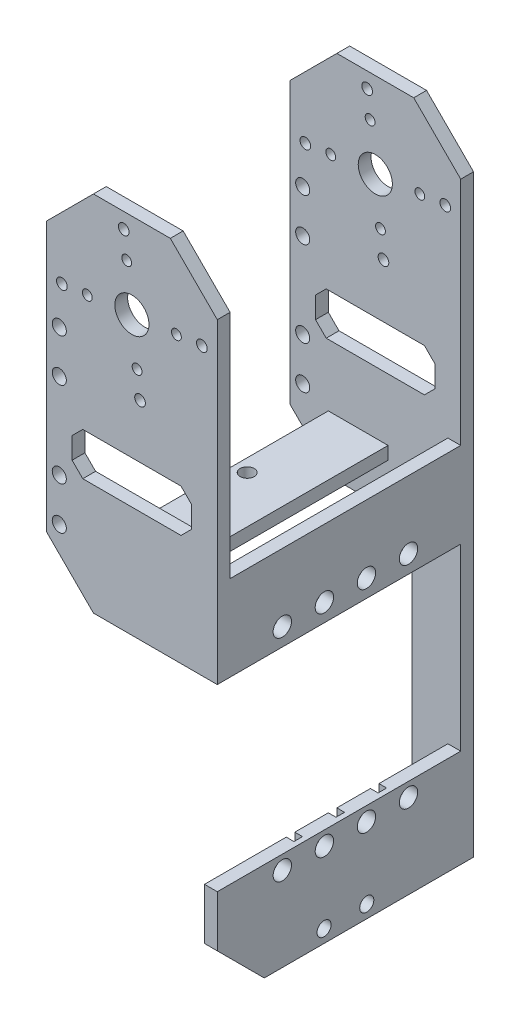
SolidWorks part; units mm, degrees
ref_plane "前视基准面" through (0, 0, 0) normal (0, 0, 1) x (1, 0, 0)
ref_plane "上视基准面" through (0, 0, 0) normal (0, 1, 0) x (1, 0, 0)
ref_plane "右视基准面" through (0, 0, 0) normal (1, 0, 0) x (0, 0, -1)
sketch "草图1" plane through (0, 0, 0) normal (0, 0, 1) x (1, 0, 0)
  line L1 (-20, -30) -> (20, -30)
  line L2 (-20, -30) -> (-20, 30)
  line L3 (-20, 30) -> (20, 30)
  line L4 (20, -30) -> (20, 30)
  line L5 (-20, -30) -> (20, 30) construction
  line L6 (-20, 30) -> (20, -30) construction
  point P0 (0, 0)
  dimension "D1" = 40
  dimension "D2" = 60
extrude "凸台-拉伸1" add sketch "草图1" along normal mid plane 60
chamfer "倒角3" distance 11 angle 45 2 edges at (20, 30, 0) (-20, 30, 0)
sketch "草图6" plane through (0, 30, 0) normal (0, 1, 0) x (1, 0, 0)
  line L0 (20, 30) -> (20, -30) construction
  line L1 (-20, -27) -> (20, -27)
  line L2 (-20, -27) -> (-20, 27)
  line L3 (-20, 27) -> (20, 27)
  line L4 (20, -27) -> (20, 27)
  line L5 (-20, -27) -> (20, 27) construction
  line L6 (-20, 27) -> (20, -27) construction
  line L7 (9, 30) -> (-9, 30) construction
  point P0 (0, 0)
  dimension "D1" = 3
extrude "切除-拉伸4" cut sketch "草图6" against normal blind 80
sketch "草图7" plane through (0, 0, 30) normal (0, 0, 1) x (1, 0, 0)
  line L0 (9, 30) -> (-9, 30) construction
  circle A0 centre (0, 10) radius 4
  dimension "D1" = 8
  dimension "D2" = 20
extrude "切除-拉伸5" cut sketch "草图7" against normal blind 80
sketch "草图9" plane through (0, 0, 30) normal (0, 0, 1) x (1, 0, 0)
  circle A0 centre (-16.3892, 8.0913) radius 1.25
  circle A1 centre (-10.4295, 8.7854) radius 1.15
  circle A2 centre (-1.2146, 20.4295) radius 1.15
  circle A3 centre (-1.9087, 26.3892) radius 1.25
  circle A4 centre (10.4295, 11.2146) radius 1.15
  circle A5 centre (16.3892, 11.9087) radius 1.25
  circle A6 centre (1.2146, -0.4295) radius 1.15
  circle A7 centre (1.9087, -6.3892) radius 1.25
  circle A8 centre (0, 10) radius 4 construction
  point P21 (0, 10)
  dimension "D2" = 2.5
  dimension "D3" = 2.3
  dimension "D1" = 4
extrude "切除-拉伸6" cut sketch "草图9" against normal blind 80
sketch "草图10" plane through (0, -30, 0) normal (0, -1, 0) x (1, 0, 0)
  line L1 (-20, 30) -> (20, 30)
  line L2 (-20, 30) -> (-20, 27)
  line L3 (-20, 27) -> (20, 27)
  line L4 (20, 30) -> (20, 27)
  line L5 (-20, -27) -> (20, -27)
  line L6 (-20, -27) -> (-20, -30)
  line L7 (-20, -30) -> (20, -30)
  line L8 (20, -27) -> (20, -30)
extrude "凸台-拉伸2" add sketch "草图10" along normal blind 90
sketch "草图11" plane through (0, 0, -27) normal (0, 0, 1) x (1, 0, 0)
  line L1 (20, -35) -> (17, -35)
  line L2 (20, -35) -> (20, -55)
  line L3 (20, -55) -> (17, -55)
  line L4 (17, -35) -> (17, -55)
  circle A0 centre (0, 10) radius 4 construction
  dimension "D3" = 45
  dimension "D1" = 20
  dimension "D2" = 3
extrude "凸台-拉伸3" add sketch "草图11" along normal up to surface (54 mm away) up to face at (-15.1392, 8.0913, 27)
sketch "草图13" plane through (0, 0, -27) normal (0, 0, 1) x (1, 0, 0)
  line L1 (20, -120) -> (17, -120)
  line L2 (20, -120) -> (20, -92.3)
  line L3 (20, -92.3) -> (17, -92.3)
  line L4 (17, -120) -> (17, -92.3)
  dimension "D1" = 3
  dimension "D2" = 37.3
extrude "凸台-拉伸4" add sketch "草图13" along normal up to surface (54 mm away) up to face at (-15.1392, 8.0913, 27)
sketch "草图12" plane through (20, 0, 0) normal (1, 0, 0) x (0, 0, -1)
  line L1 (-27, -55) -> (27, -55) construction
  line L2 (0, 22) -> (0, -22) construction
  circle A0 centre (-14.775, -50.85) radius 2.15
  circle A1 centre (-4.925, -50.85) radius 2.15
  circle A4 centre (-14.775, -100.27) radius 2.15
  circle A5 centre (-4.925, -100.27) radius 2.15
  circle A6 centre (4.925, -100.27) radius 2.15
  circle A7 centre (14.775, -100.27) radius 2.15
  circle A8 centre (4.925, -50.85) radius 2.15
  circle A9 centre (14.775, -50.85) radius 2.15
  dimension "D1" = 9.85
  dimension "D2" = 4.3
  dimension "D3" = 4.3
  dimension "D4" = 4.3
  dimension "D5" = 4.15
  dimension "D6" = 49.42
  dimension "D7" = 9.85
  dimension "D8" = 4.3
extrude "切除-拉伸7" cut sketch "草图12" against normal blind 10
sketch "草图15" plane through (0, 0, -27) normal (0, 0, 1) x (1, 0, 0)
  line L1 (20, -55) -> (-20, -55)
  line L2 (20, -55) -> (20, -97)
  line L3 (20, -97) -> (-20, -97)
  line L4 (-20, -55) -> (-20, -97)
  dimension "D1" = 40
  dimension "D2" = 42
extrude "切除-拉伸8" cut sketch "草图15" along normal blind 80
sketch "草图16" plane through (0, 0, 27) normal (0, 0, -1) x (-1, 0, 0)
  line L1 (-17, -97) -> (20, -97)
  line L2 (-17, -97) -> (-17, -120)
  line L3 (-17, -120) -> (20, -120)
  line L4 (20, -97) -> (20, -120)
extrude "切除-拉伸9" cut sketch "草图16" against normal blind 40
sketch "草图17" plane through (17, 0, 0) normal (-1, 0, 0) x (0, 0, 1)
  line L0 (-4.925, -50.85) -> (4.925, -50.85) construction
  line L1 (27, -55) -> (-27, -55) construction
  line L2 (-1, -46.7) -> (1, -46.7)
  line L3 (-1, -46.7) -> (-1, -55)
  line L4 (-1, -55) -> (1, -55)
  line L5 (1, -46.7) -> (1, -55)
  line L6 (-1, -46.7) -> (1, -55) construction
  line L7 (-1, -55) -> (1, -46.7) construction
  line L8 (-14.775, -50.85) -> (-4.925, -50.85) construction
  line L9 (0, -22) -> (0, 22) construction
  line L10 (-10.85, -46.7) -> (-8.85, -46.7)
  line L11 (-10.85, -46.7) -> (-10.85, -55)
  line L12 (-10.85, -55) -> (-8.85, -55)
  line L13 (-8.85, -46.7) -> (-8.85, -55)
  line L14 (-10.85, -46.7) -> (-8.85, -55) construction
  line L15 (-10.85, -55) -> (-8.85, -46.7) construction
  line L16 (10.85, -55) -> (8.85, -46.7) construction
  line L17 (10.85, -46.7) -> (8.85, -55) construction
  line L18 (8.85, -46.7) -> (8.85, -55)
  line L19 (10.85, -55) -> (8.85, -55)
  line L20 (10.85, -46.7) -> (10.85, -55)
  line L21 (10.85, -46.7) -> (8.85, -46.7)
  line L22 (-27, -55) -> (-27, -97) construction
  line L23 (-27, -120) -> (-27, 19) construction
  line L24 (-27, -35) -> (-27, -55) construction
  line L25 (-27, -76) -> (29.9811, -76) construction
  line L26 (10.85, -105.3) -> (8.85, -97) construction
  line L27 (10.85, -97) -> (8.85, -105.3) construction
  line L28 (-10.85, -97) -> (-8.85, -105.3) construction
  line L29 (-10.85, -105.3) -> (-8.85, -97) construction
  line L30 (-14.775, -101.15) -> (-4.925, -101.15) construction
  line L31 (-1, -97) -> (1, -105.3) construction
  line L32 (-1, -105.3) -> (1, -97) construction
  line L33 (-4.925, -101.15) -> (4.925, -101.15) construction
  line L34 (10.85, -105.3) -> (8.85, -105.3)
  line L35 (10.85, -105.3) -> (10.85, -97)
  line L36 (10.85, -97) -> (8.85, -97)
  line L37 (8.85, -105.3) -> (8.85, -97)
  line L38 (-8.85, -105.3) -> (-8.85, -97)
  line L39 (-10.85, -97) -> (-8.85, -97)
  line L40 (-10.85, -105.3) -> (-10.85, -97)
  line L41 (-10.85, -105.3) -> (-8.85, -105.3)
  line L42 (1, -105.3) -> (1, -97)
  line L43 (-1, -97) -> (1, -97)
  line L44 (-1, -105.3) -> (-1, -97)
  line L45 (-1, -105.3) -> (1, -105.3)
  point P4 (0, -50.85)
  point P12 (-9.85, -50.85)
  point P24 (9.85, -50.85)
  point P49 (9.85, -101.15)
  point P50 (-9.85, -101.15)
  point P51 (0, -101.15)
  dimension "D1" = 2
  dimension "D2" = 2
extrude "切除-拉伸10" cut sketch "草图17" against normal blind 1.8
sketch "草图18" plane through (17, 0, 0) normal (-1, 0, 0) x (0, 0, 1)
  line L0 (27, -35) -> (27, -55) construction
  line L1 (-27, -46.5) -> (27, -46.5)
  line L2 (-27, -46.5) -> (-27, -43.5)
  line L3 (-27, -43.5) -> (27, -43.5)
  line L4 (27, -46.5) -> (27, -43.5)
  line L5 (-27, -46.5) -> (27, -43.5) construction
  line L6 (-27, -43.5) -> (27, -46.5) construction
  point P0 (0, -45)
  dimension "D1" = 3
  dimension "D2" = 45
extrude "凸台-拉伸5" add sketch "草图18" along normal blind 28
sketch "草图19" plane through (0, -43.5, 0) normal (0, 1, 0) x (1, 0, 0)
  line L0 (-9, -27) -> (9, -27) construction
  line L1 (17, 27) -> (3, 27)
  line L2 (17, 27) -> (17, -27)
  line L3 (17, -27) -> (3, -27)
  line L4 (3, 27) -> (3, -27)
  dimension "D1" = 14
extrude "切除-拉伸11" cut sketch "草图19" against normal blind 11.5
chamfer "倒角4" distance 11 angle 45 3 edges at (-20, -120, -28.5) (-20, -55, 28.5) (18.5, -120, 30)
sketch "草图23" plane through (0, 0, -27) normal (0, 0, 1) x (1, 0, 0)
  line L0 (-20, -109) -> (-20, 19) construction
  line L1 (-20, -77) -> (-17, -77)
  line L2 (-20, -77) -> (-20, -95)
  line L3 (-20, -95) -> (-17, -95)
  line L4 (-17, -77) -> (-17, -95)
  point P6 (-20, -86)
  dimension "D1" = 3
  dimension "D2" = 18
  dimension "D3" = 14
sketch "草图24" plane through (0, 0, -27) normal (0, 0, 1) x (1, 0, 0)
  line L0 (-20, -109) -> (-20, 19) construction
  circle A0 centre (-14, -79) radius 1.7
  circle A1 centre (-14, -89) radius 1.7
  dimension "D1" = 3.4
  dimension "D2" = 3.4
  dimension "D3" = 10
  dimension "D4" = 6
  dimension "D5" = 20
extrude "切除-拉伸12" cut sketch "草图24" against normal blind 35
sketch "草图25" plane through (0, 0, -27) normal (0, 0, 1) x (1, 0, 0)
  line L0 (17, -120) -> (-9, -120) construction
  line L1 (17, -97) -> (17, -120) construction
  circle A0 centre (3, -116) radius 1.65
  circle A1 centre (13, -116) radius 1.65
  dimension "D1" = 3.3
  dimension "D2" = 4
  dimension "D3" = 14
  dimension "D4" = 10
  dimension "D5" = 3.3
extrude "切除-拉伸13" cut sketch "草图25" against normal blind 35
sketch "草图27" plane through (0, 0, -30) normal (0, 0, -1) x (-1, 0, 0)
  line L0 (-14, -21.5) -> (-11.5, -19)
  line L1 (-11.5, -29) -> (11.5, -29)
  line L2 (-14, -26.5) -> (-14, -21.5)
  line L3 (-11.5, -19) -> (11.5, -19)
  line L4 (14, -26.5) -> (14, -21.5)
  line L5 (-14, -29) -> (14, -19) construction
  line L6 (-14, -19) -> (14, -29) construction
  line L7 (-14, -26.5) -> (-11.5, -29)
  line L8 (11.5, -29) -> (14, -26.5)
  line L9 (11.5, -19) -> (14, -21.5)
  point P0 (0, -24)
  dimension "D1" = 28
  dimension "D2" = 10
  dimension "D3" = 24
extrude "切除-拉伸14" cut sketch "草图27" against normal blind 65
sketch "草图28" plane through (0, 0, -30) normal (0, 0, -1) x (-1, 0, 0)
  line L0 (-20, -120) -> (-20, 19) construction
  line L1 (-4, -105) -> (-1, -105)
  line L2 (-7, -102) -> (-7, -84)
  line L3 (-4, -81) -> (-1, -81)
  line L4 (-1, -105) -> (-1, -81)
  line L5 (-7, -105) -> (-1, -81) construction
  line L6 (-7, -81) -> (-1, -105) construction
  line L7 (7.5, -70) -> (9.5, -70)
  line L8 (7.5, -70) -> (7.5, -48)
  line L9 (7.5, -48) -> (9.5, -48)
  line L10 (12.5, -67) -> (12.5, -51)
  line L11 (7.5, -70) -> (12.5, -48) construction
  line L12 (7.5, -48) -> (12.5, -70) construction
  line L13 (20, 19) -> (20, -109) construction
  line L14 (9, -120) -> (-20, -120) construction
  line L15 (-7, -102) -> (-4, -105)
  line L16 (-7, -84) -> (-4, -81)
  line L17 (9.5, -48) -> (12.5, -51)
  line L18 (9.5, -70) -> (12.5, -67)
  point P0 (-4, -93)
  point P5 (10, -59)
  dimension "D1" = 16
  dimension "D2" = 6
  dimension "D3" = 10
  dimension "D4" = 15
  dimension "D5" = 50
  dimension "D6" = 5
  dimension "D7" = 24
  dimension "D8" = 22
extrude "切除-拉伸15" cut sketch "草图28" against normal blind 45
sketch "草图29" plane through (0, 0, -27) normal (0, 0, 1) x (1, 0, 0)
  line L0 (17, -120) -> (-9, -120) construction
  line L1 (8.5508, -120) -> (-24.9514, -120)
  line L2 (8.5508, -120) -> (8.5508, -56.6132)
  line L3 (8.5508, -56.6132) -> (-24.9514, -56.6132)
  line L4 (-24.9514, -120) -> (-24.9514, -56.6132)
extrude "切除-拉伸16" cut sketch "草图29" against normal blind 10
sketch "草图30" plane through (0, 0, 30) normal (0, 0, 1) x (1, 0, 0)
  line L0 (-20, 19) -> (-20, -44) construction
  circle A0 centre (-17, -31) radius 1.65
  circle A1 centre (-17, -41) radius 1.65
  dimension "D1" = 3
  dimension "D2" = 3.3
  dimension "D3" = 3.3
  dimension "D4" = 10
  dimension "D5" = 3
extrude "切除-拉伸17" cut sketch "草图30" against normal mid plane 140
sketch "草图31" plane through (0, 0, 30) normal (0, 0, 1) x (1, 0, 0)
  line L0 (-20, 19) -> (-20, -44) construction
  circle A0 centre (-17, -11) radius 1.65
  circle A1 centre (-17, -1) radius 1.65
  circle A2 centre (-17, -31) radius 1.65 construction
  dimension "D1" = 3.3
  dimension "D2" = 3.3
  dimension "D3" = 10
  dimension "D4" = 3
  dimension "D5" = 20
extrude "切除-拉伸18" cut sketch "草图31" against normal blind 70
sketch "草图32" plane through (0, -43.5, 0) normal (0, 1, 0) x (1, 0, 0)
  line L0 (-22, 0) -> (22, 0) construction
  line L1 (-11, -27) -> (-11, 27) construction
  circle A0 centre (-8, 5) radius 1.65
  circle A1 centre (-8, -5) radius 1.65
  dimension "D1" = 3.3
  dimension "D2" = 10
  dimension "D3" = 3
extrude "切除-拉伸19" cut sketch "草图32" against normal blind 70
sketch "草图33" plane through (20, 0, 0) normal (1, 0, 0) x (0, 0, -1)
  line L0 (0, 22) -> (0, -22) construction
  line L1 (30, -120) -> (-19, -120) construction
  circle A0 centre (-5, -117) radius 1.65
  circle A1 centre (5, -117) radius 1.65
  dimension "D1" = 3
  dimension "D2" = 10
  dimension "D3" = 3.3
extrude "切除-拉伸20" cut sketch "草图33" against normal blind 30
sketch "草图34" plane through (0, 0, -30) normal (0, 0, -1) x (-1, 0, 0)
  line L0 (7.5, -56.6132) -> (12.5, -56.6132)
  line L1 (12.5, -56.6132) -> (12.5, -48)
  line L2 (12.5, -48) -> (7.5, -48)
  line L3 (7.5, -48) -> (7.5, -56.6132)
extrude "凸台-拉伸6" add sketch "草图34" against normal up to surface (3 mm away) up to face at (-18.65, -11, -27)
chamfer "倒角5" distance 10 angle 45 1 edges at (-20, -56.6132, -28.5)
chamfer "倒角6" distance 8 angle 45 1 edges at (8.5508, -56.6132, -28.5)
